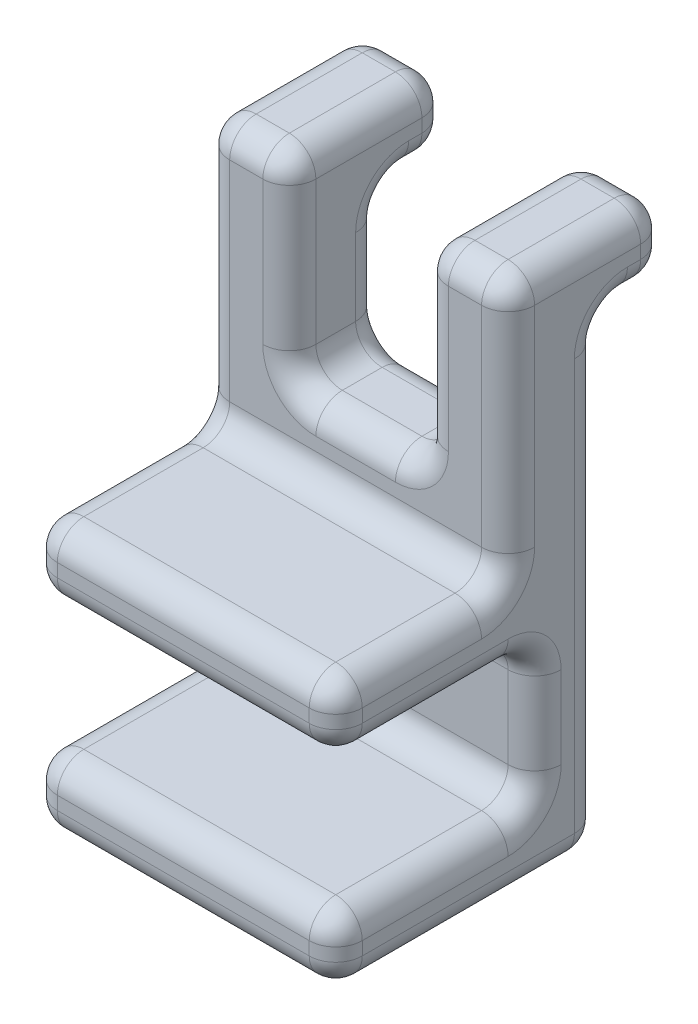
SolidWorks part; units mm, degrees
ref_plane "Front Plane" through (0, 0, 0) normal (0, 0, 1) x (1, 0, 0)
ref_plane "Top Plane" through (0, 0, 0) normal (0, 1, 0) x (1, 0, 0)
ref_plane "Right Plane" through (0, 0, 0) normal (1, 0, 0) x (0, 0, -1)
sketch "Sketch1" plane through (0, 0, 0) normal (0, 0, 1) x (1, 0, 0)
  line L1 (0, 0) -> (-23, 0)
  line L2 (0, 0) -> (0, 40)
  line L3 (0, 40) -> (-23, 40)
  line L4 (-23, 0) -> (-23, 40)
  dimension "D1" = 40
  dimension "D2" = 23
extrude "Boss-Extrude1" add sketch "Sketch1" along normal blind 20
sketch "Sketch2" plane through (0, 0, 0) normal (1, 0, 0) x (0, 0, -1)
  line L0 (-20, 0) -> (-20, 40) construction
  line L1 (-20, 15.2) -> (-5, 15.2)
  line L2 (-20, 15.2) -> (-20, 5)
  line L3 (-20, 5) -> (-5, 5)
  line L4 (-5, 15.2) -> (-5, 5)
  line L5 (-20, 0) -> (0, 0) construction
  line L6 (0, 0) -> (0, 40) construction
  dimension "10,5" = 10.2
  dimension "D1" = 5
  dimension "D2" = 5
extrude "Cut-Extrude1" cut sketch "Sketch2" against normal through all
fillet "Fillet1" radius 2 8 edges at (-23, 5, 12.5) (0, 5, 12.5) (-23, 15.2, 12.5) (0, 15.2, 12.5) (-11.5, 5, 5) (-23, 10.1, 5) (-11.5, 15.2, 5) (0, 10.1, 5)
sketch "Sketch4" plane through (-23, 0, 0) normal (-1, 0, 0) x (0, 0, 1)
  line L1 (20, 20.2) -> (7, 20.2)
  line L2 (20, 20.2) -> (20, 40)
  line L3 (20, 40) -> (7, 40)
  line L4 (7, 20.2) -> (7, 40)
  line L12 (20, 15.2) -> (7, 15.2) construction
  dimension "D1" = 5
extrude "Cut-Extrude3" cut sketch "Sketch4" against normal through all
sketch "Sketch6" plane through (0, 0, 0) normal (0, 0, -1) x (-1, 0, 0)
  line L1 (0, 40) -> (23, 40)
  line L2 (0, 40) -> (0, 35)
  line L3 (0, 35) -> (23, 35)
  line L4 (23, 40) -> (23, 35)
  dimension "D1" = 5
extrude "Boss-Extrude2" add sketch "Sketch6" along normal blind 5
sketch "Sketch5" plane through (0, 0, 0) normal (0, 0, -1) x (-1, 0, 0)
  line L0 (23, 35) -> (23, 0) construction
  line L1 (6.5, 40) -> (16.5, 40)
  line L2 (6.5, 40) -> (6.5, 25.2)
  line L3 (6.5, 25.2) -> (16.5, 25.2)
  line L4 (16.5, 40) -> (16.5, 25.2)
  line L5 (0, 0) -> (0, 35) construction
  line L6 (6.5, 25.2) -> (16.5, 25.2) construction
  line L7 (23, 40) -> (0, 40) construction
  line L8 (0, 35) -> (23, 35) construction
  line L9 (0, 35) -> (23, 35) construction
  line L11 (0, 20.2) -> (23, 20.2) construction
  point P16 (11.5, 25.2)
  point P17 (11.5, 35)
  dimension "D1" = 10
  dimension "D2" = 5
extrude "Cut-Extrude4" cut sketch "Sketch5" against normal up to next and the other way through all
fillet "Fillet11" radius 2 50 edges at (-6.5, 25.2, 3.5) (-16.5, 25.2, 3.5) (-16.5, 40, 1) (-6.5, 40, 1) (-0.5858, 4.4142, 20) (-22.4142, 4.4142, 20) (-0.5858, 15.7858, 20) (-22.4142, 15.7858, 20) (-11.5, 20.2, 20) (-3.25, 40, 7) (-11.5, 20.2, 7) (-19.75, 40, 7) (-16.5, 32.6, 7) (-11.5, 25.2, 7) (-6.5, 32.6, 7) (0, 40, 1) (0, 1.5, 20) (0, 18.7, 20) (0, 20.2, 13.5) (0, 30.1, 7) (-11.5, 15.2, 20) (-11.5, 5, 20) (-11.5, 0, 20) (0, 0, 10) (-23, 1.5, 20) (-23, 0, 10) (-23, 40, 1) (-23, 30.1, 7) (-23, 20.2, 13.5) (-23, 18.7, 20) (-23, 37.5, -5) (-16.5, 37.5, -5) (-19.75, 40, -5) (-19.75, 35, -5) (-23, 35, -2.5) (-16.5, 35, -2.5) (0, 35, -2.5) (-6.5, 35, -2.5) (0, 37.5, -5) (-3.25, 40, -5) (-6.5, 37.5, -5) (-3.25, 35, -5) (-11.5, 25.2, 0) (-16.5, 30.1, 0) (-19.75, 35, 0) (-23, 17.5, 0) (-11.5, 0, 0) (0, 17.5, 0) (-3.25, 35, 0) (-6.5, 30.1, 0)
equation "\"A\" = 10.2mm"
equation "\"10,5@Sketch2\" = \"A\""
